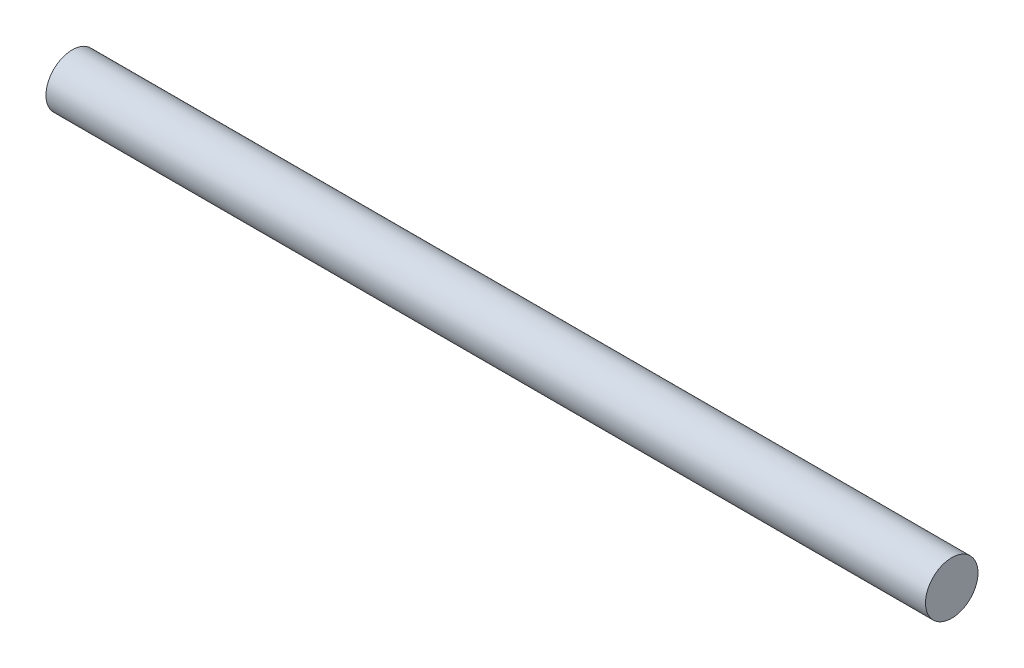
SolidWorks part; units mm, degrees
ref_plane "Front Plane" through (0, 0, 0) normal (0, 0, 1) x (1, 0, 0)
ref_plane "Top Plane" through (0, 0, 0) normal (0, 1, 0) x (1, 0, 0)
ref_plane "Right Plane" through (0, 0, 0) normal (1, 0, 0) x (0, 0, -1)
sketch "Sketch1" plane through (0, 0, 0) normal (1, 0, 0) x (0, 0, -1)
  circle A0 centre (0, 0) radius 4
  dimension "D1" = 8
extrude "Boss-Extrude1" add sketch "Sketch1" along normal blind 134
